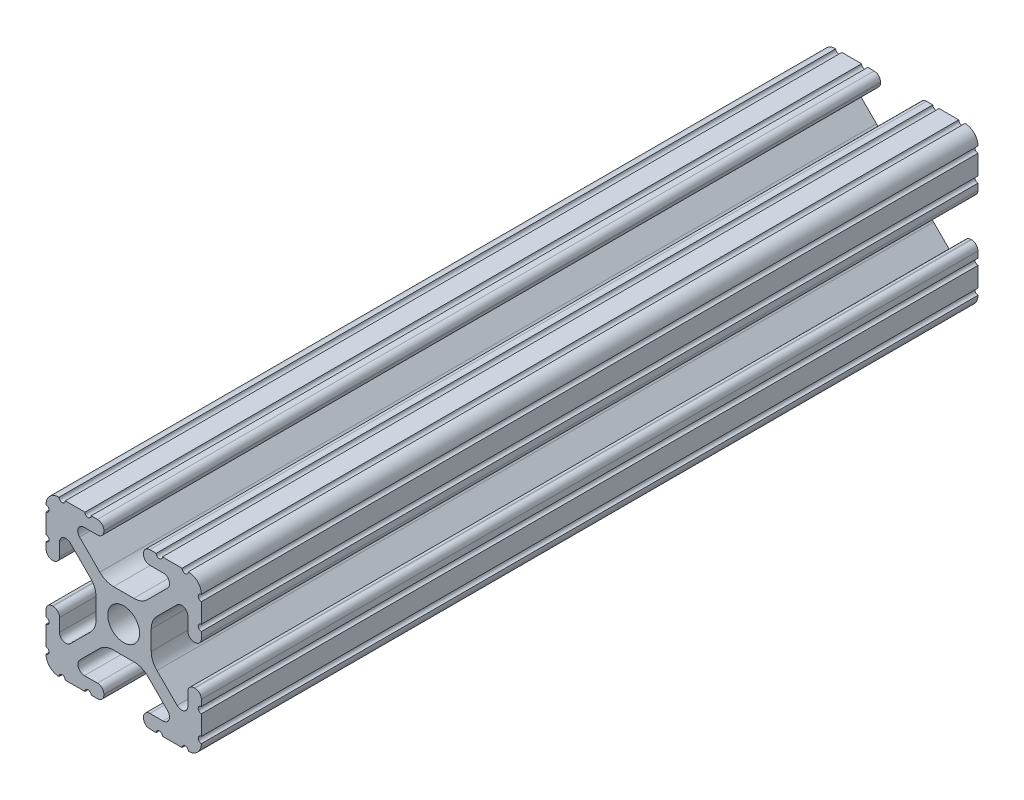
SolidWorks part; units mm, degrees
ref_plane "Front Plane" through (0, 0, 0) normal (0, 0, 1) x (1, 0, 0)
ref_plane "Top Plane" through (0, 0, 0) normal (0, 1, 0) x (1, 0, 0)
ref_plane "Right Plane" through (0, 0, 0) normal (1, 0, 0) x (0, 0, -1)
sketch "Sketch1" plane through (0, 0, 0) normal (0, 0, 1) x (1, 0, 0)
  line L88 (-7.1797, -8.6452) -> (-3.9523, -5.4237)
  line L89 (-1.7093, -4.4958) -> (1.7093, -4.4958)
  line L90 (3.9523, -5.4237) -> (7.1797, -8.6452)
  line L91 (6.4164, -10.4902) -> (4.2875, -10.4902)
  line L92 (3.2385, -11.5392) -> (3.2385, -11.651)
  line L93 (4.2875, -12.7) -> (5.3171, -12.7)
  line L94 (6.3331, -12.7) -> (9.5504, -12.7)
  line L95 (12.7, -9.5504) -> (12.7, -6.3331)
  line L96 (12.7, -5.3171) -> (12.7, -4.2875)
  line L97 (11.651, -3.2385) -> (11.5392, -3.2385)
  line L98 (10.4902, -4.2875) -> (10.4902, -6.4021)
  line L99 (8.7371, -7.1294) -> (5.441, -3.8408)
  line L100 (4.5085, -1.5932) -> (4.5085, 1.5932)
  line L101 (5.441, 3.8408) -> (8.7371, 7.1294)
  line L102 (10.4902, 6.4021) -> (10.4902, 4.2875)
  line L103 (11.5392, 3.2385) -> (11.651, 3.2385)
  line L104 (12.7, 4.2875) -> (12.7, 5.3171)
  line L105 (12.7, 6.3331) -> (12.7, 9.5504)
  line L106 (9.5504, 12.7) -> (6.3331, 12.7)
  line L107 (5.3171, 12.7) -> (4.2875, 12.7)
  line L108 (3.2385, 11.651) -> (3.2385, 11.5392)
  line L109 (4.2875, 10.4902) -> (6.4768, 10.4902)
  line L110 (7.207, 8.7244) -> (3.8983, 5.4232)
  line L111 (1.6558, 4.4958) -> (-1.6558, 4.4958)
  line L112 (-3.8983, 5.4232) -> (-7.207, 8.7244)
  line L113 (-6.4768, 10.4902) -> (-4.2875, 10.4902)
  line L114 (-3.2385, 11.5392) -> (-3.2385, 11.651)
  line L115 (-4.2875, 12.7) -> (-5.3171, 12.7)
  line L116 (-6.3331, 12.7) -> (-9.5504, 12.7)
  line L117 (-12.7, 9.5504) -> (-12.7, 6.3331)
  line L118 (-12.7, 5.3171) -> (-12.7, 4.2875)
  line L119 (-11.651, 3.2385) -> (-11.5392, 3.2385)
  line L120 (-10.4902, 4.2875) -> (-10.4902, 6.4021)
  line L121 (-8.7371, 7.1294) -> (-5.441, 3.8408)
  line L122 (-4.5085, 1.5932) -> (-4.5085, -1.5932)
  line L123 (-5.441, -3.8408) -> (-8.7371, -7.1294)
  line L124 (-10.4902, -6.4021) -> (-10.4902, -4.2875)
  line L125 (-11.5392, -3.2385) -> (-11.651, -3.2385)
  line L126 (-12.7, -4.2875) -> (-12.7, -5.3171)
  line L127 (-12.7, -6.3331) -> (-12.7, -9.5504)
  line L128 (-9.5504, -12.7) -> (-6.3331, -12.7)
  line L129 (-5.3171, -12.7) -> (-4.2875, -12.7)
  line L130 (-3.2385, -11.651) -> (-3.2385, -11.5392)
  line L131 (-4.2875, -10.4902) -> (-6.4164, -10.4902)
  circle A1 centre (0, 0) radius 2.6035
  arc A104 (-7.1797, -8.6452) -> (-6.4164, -10.4902) centre (-6.4164, -9.4098) ccw
  arc A105 (-1.7093, -4.4958) -> (-3.9523, -5.4237) centre (-1.7093, -7.6708) ccw
  arc A106 (3.9523, -5.4237) -> (1.7093, -4.4958) centre (1.7093, -7.6708) ccw
  arc A107 (6.4164, -10.4902) -> (7.1797, -8.6452) centre (6.4164, -9.4098) ccw
  arc A108 (4.2875, -10.4902) -> (3.2385, -11.5392) centre (4.2875, -11.5392) ccw
  arc A109 (3.2385, -11.651) -> (4.2875, -12.7) centre (4.2875, -11.651) ccw
  arc A110 (6.3331, -12.7) -> (5.3171, -12.7) centre (5.8251, -12.7) ccw
  arc A111 (10.5664, -12.6998) -> (9.5504, -12.7) centre (10.0584, -12.7) ccw
  arc A112 (10.5664, -12.6998) -> (12.6998, -10.5664) centre (10.5918, -10.5918) ccw
  arc A113 (12.7, -9.5504) -> (12.6998, -10.5664) centre (12.7, -10.0584) ccw
  arc A114 (12.7, -5.3171) -> (12.7, -6.3331) centre (12.7, -5.8251) ccw
  arc A115 (12.7, -4.2875) -> (11.651, -3.2385) centre (11.651, -4.2875) ccw
  arc A116 (11.5392, -3.2385) -> (10.4902, -4.2875) centre (11.5392, -4.2875) ccw
  arc A117 (8.7371, -7.1294) -> (10.4902, -6.4021) centre (9.4628, -6.4021) ccw
  arc A118 (4.5085, -1.5932) -> (5.441, -3.8408) centre (7.6835, -1.5932) ccw
  arc A119 (5.441, 3.8408) -> (4.5085, 1.5932) centre (7.6835, 1.5932) ccw
  arc A120 (10.4902, 6.4021) -> (8.7371, 7.1294) centre (9.4628, 6.4021) ccw
  arc A121 (10.4902, 4.2875) -> (11.5392, 3.2385) centre (11.5392, 4.2875) ccw
  arc A122 (11.651, 3.2385) -> (12.7, 4.2875) centre (11.651, 4.2875) ccw
  arc A123 (12.7, 6.3331) -> (12.7, 5.3171) centre (12.7, 5.8251) ccw
  arc A124 (12.6998, 10.5664) -> (12.7, 9.5504) centre (12.7, 10.0584) ccw
  arc A125 (12.6998, 10.5664) -> (10.5664, 12.6998) centre (10.5918, 10.5918) ccw
  arc A126 (9.5504, 12.7) -> (10.5664, 12.6998) centre (10.0584, 12.7) ccw
  arc A127 (5.3171, 12.7) -> (6.3331, 12.7) centre (5.8251, 12.7) ccw
  arc A128 (4.2875, 12.7) -> (3.2385, 11.651) centre (4.2875, 11.651) ccw
  arc A129 (3.2385, 11.5392) -> (4.2875, 10.4902) centre (4.2875, 11.5392) ccw
  arc A130 (7.207, 8.7244) -> (6.4768, 10.4902) centre (6.4768, 9.4563) ccw
  arc A131 (1.6558, 4.4958) -> (3.8983, 5.4232) centre (1.6558, 7.6708) ccw
  arc A132 (-3.8983, 5.4232) -> (-1.6558, 4.4958) centre (-1.6558, 7.6708) ccw
  arc A133 (-6.4768, 10.4902) -> (-7.207, 8.7244) centre (-6.4768, 9.4563) ccw
  arc A134 (-4.2875, 10.4902) -> (-3.2385, 11.5392) centre (-4.2875, 11.5392) ccw
  arc A135 (-3.2385, 11.651) -> (-4.2875, 12.7) centre (-4.2875, 11.651) ccw
  arc A136 (-6.3331, 12.7) -> (-5.3171, 12.7) centre (-5.8251, 12.7) ccw
  arc A137 (-10.5664, 12.6998) -> (-9.5504, 12.7) centre (-10.0584, 12.7) ccw
  arc A138 (-10.5664, 12.6998) -> (-12.6998, 10.5664) centre (-10.5918, 10.5918) ccw
  arc A139 (-12.7, 9.5504) -> (-12.6998, 10.5664) centre (-12.7, 10.0584) ccw
  arc A140 (-12.7, 5.3171) -> (-12.7, 6.3331) centre (-12.7, 5.8251) ccw
  arc A141 (-12.7, 4.2875) -> (-11.651, 3.2385) centre (-11.651, 4.2875) ccw
  arc A142 (-11.5392, 3.2385) -> (-10.4902, 4.2875) centre (-11.5392, 4.2875) ccw
  arc A143 (-8.7371, 7.1294) -> (-10.4902, 6.4021) centre (-9.4628, 6.4021) ccw
  arc A144 (-4.5085, 1.5932) -> (-5.441, 3.8408) centre (-7.6835, 1.5932) ccw
  arc A145 (-5.441, -3.8408) -> (-4.5085, -1.5932) centre (-7.6835, -1.5932) ccw
  arc A146 (-10.4902, -6.4021) -> (-8.7371, -7.1294) centre (-9.4628, -6.4021) ccw
  arc A147 (-10.4902, -4.2875) -> (-11.5392, -3.2385) centre (-11.5392, -4.2875) ccw
  arc A148 (-11.651, -3.2385) -> (-12.7, -4.2875) centre (-11.651, -4.2875) ccw
  arc A149 (-12.7, -6.3331) -> (-12.7, -5.3171) centre (-12.7, -5.8251) ccw
  arc A150 (-12.6998, -10.5664) -> (-12.7, -9.5504) centre (-12.7, -10.0584) ccw
  arc A151 (-12.6998, -10.5664) -> (-10.5664, -12.6998) centre (-10.5918, -10.5918) ccw
  arc A152 (-9.5504, -12.7) -> (-10.5664, -12.6998) centre (-10.0584, -12.7) ccw
  arc A153 (-5.3171, -12.7) -> (-6.3331, -12.7) centre (-5.8251, -12.7) ccw
  arc A154 (-4.2875, -12.7) -> (-3.2385, -11.651) centre (-4.2875, -11.651) ccw
  arc A155 (-3.2385, -11.5392) -> (-4.2875, -10.4902) centre (-4.2875, -11.5392) ccw
extrude "Boss-Extrude1" add sketch "Sketch1" along normal mid plane 127
